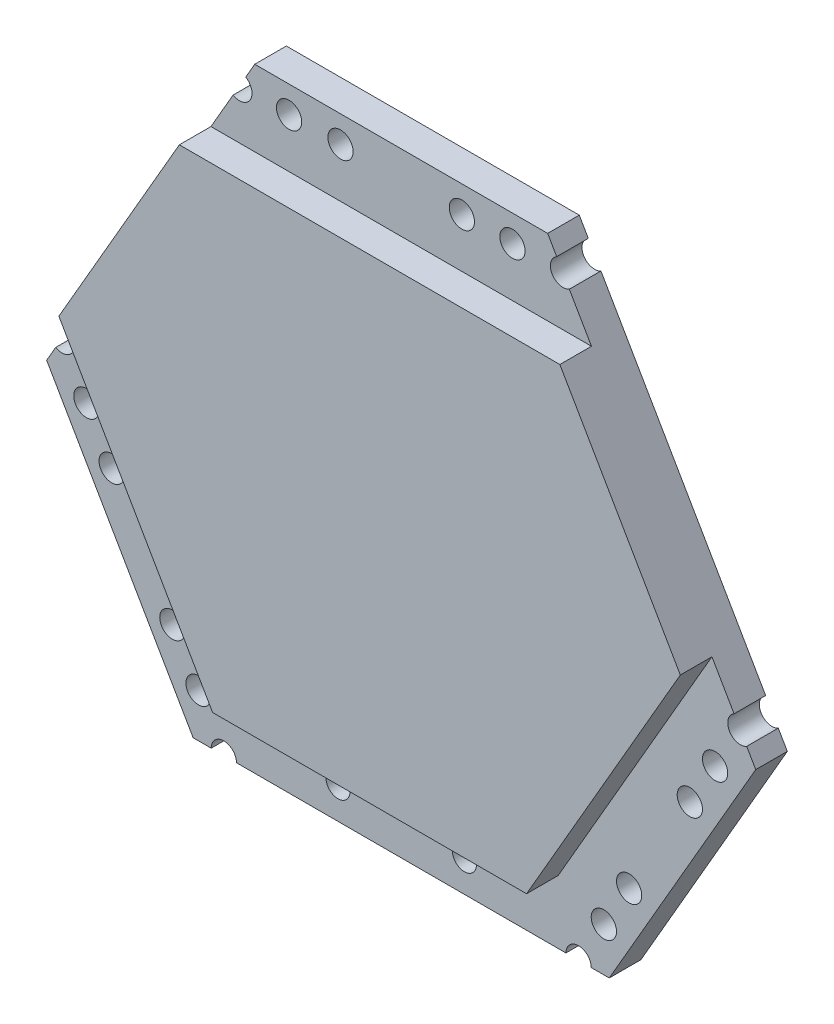
SolidWorks part; units mm, degrees
material "ABS"
ref_plane "前基準面" through (0, 0, 0) normal (0, 0, 1) x (1, 0, 0)
ref_plane "上基準面" through (0, 0, 0) normal (0, 1, 0) x (1, 0, 0)
ref_plane "右基準面" through (0, 0, 0) normal (1, 0, 0) x (0, 0, -1)
sketch "草圖1" plane through (0, 0, 0) normal (0, 0, 1) x (1, 0, 0)
  line L0 (29.3027, 33.7186) -> (37.3027, 33.7186) construction
  line L1 (45.3027, 33.7186) -> (-5.8973, 33.7186)
  line L2 (-5.8973, 33.7186) -> (-33.9573, -14.8827)
  line L3 (-33.9573, -14.8827) -> (-5.8973, 33.7186)
  line L7 (-33.9573, -14.8827) -> (-8.3573, -59.2232)
  line L8 (-8.3573, -59.2232) -> (-33.9573, -14.8827)
  line L9 (-8.3573, -59.2232) -> (47.7627, -59.2232)
  line L10 (47.7627, -59.2232) -> (73.3627, -14.8827)
  line L11 (73.3627, -14.8827) -> (45.3027, 33.7186)
  line L12 (73.3627, -14.8827) -> (69.3627, -21.8109) construction
  line L13 (-10.3973, 37.9244) -> (49.8027, 37.9244)
  line L14 (-10.3973, 37.9244) -> (-10.3973, 25.9244)
  line L15 (-10.3973, 25.9244) -> (49.8027, 25.9244)
  line L16 (49.8027, 37.9244) -> (49.8027, 25.9244)
  line L17 (-29.4573, -7.0885) -> (0.6427, -59.2232)
  line L18 (0.6427, -59.2232) -> (-9.7496, -65.2232)
  line L19 (-9.7496, -65.2232) -> (-39.8496, -13.0885)
  line L20 (-39.8496, -13.0885) -> (-29.4573, -7.0885)
  line L21 (55.7627, -45.3668) -> (51.7627, -52.295) construction
  line L22 (68.8627, -7.0885) -> (38.7627, -59.2232)
  line L23 (38.7627, -59.2232) -> (49.155, -65.2232)
  line L24 (49.155, -65.2232) -> (79.255, -13.0885)
  line L25 (79.255, -13.0885) -> (68.8627, -7.0885)
  circle A0 centre (-5.8973, 33.7186) radius 2
  circle A1 centre (1.9623, 33.7186) radius 2
  circle A2 centre (10.1027, 33.7186) radius 2
  circle A4 centre (29.3027, 33.7186) radius 2
  circle A8 centre (-33.9573, -14.8827) radius 2
  circle A9 centre (-30.0977, -21.8109) radius 2
  circle A10 centre (-26.0977, -28.7391) radius 2
  circle A12 centre (-16.4977, -45.3668) radius 2
  circle A13 centre (-12.3573, -52.295) radius 2
  circle A14 centre (-8.3573, -59.2232) radius 2
  circle A15 centre (47.7627, -59.2232) radius 2
  circle A18 centre (55.7627, -45.3668) radius 2
  circle A22 centre (37.3027, 33.7186) radius 2
  circle A23 centre (45.3027, 33.7186) radius 2
  circle A24 centre (73.3627, -14.8827) radius 2
  circle A25 centre (69.3627, -21.8109) radius 2
  circle A26 centre (65.3627, -28.7391) radius 2
  circle A27 centre (51.7627, -52.295) radius 2
  dimension "D1" = 4
  dimension "D6" = 4
  dimension "D10" = 4
  dimension "D13" = 19.2
  dimension "D11" = 4
  dimension "D15" = 19.2
  dimension "D7" = 19.2
  dimension "D17" = 8
  dimension "D2" = 8
  dimension "D3" = 120
  dimension "D4" = 120
  dimension "D5" = 56.12
  dimension "D8" = 120
  dimension "D9" = 56.12
  dimension "D12" = 8
  dimension "D16" = 56.12
  dimension "D18" = 4.5
  dimension "D19" = 4.5
  dimension "D20" = 60.2
  dimension "D21" = 12
  dimension "D22" = 90
  dimension "D23" = 180
  dimension "D24" = 12
  dimension "D25" = 4.5
  dimension "D26" = 4.5
  dimension "D27" = 8
  dimension "D28" = 12
  dimension "D29" = 60.2
  dimension "D30" = 90
  dimension "D31" = 4.5
  dimension "D14" = 3
extrude "填料-伸長4" add sketch "草圖1" along normal blind 10 contours L22 L11 L15 L3 L17 L9 | A23 L1 A22 A4 A2 A1 A0 L3 L15 L11 | A23 L11 L16 L13 L14 L3 A0 L1 A1 A2 A4 A22 | A14 L8 A13 A12 A10 A9 A8 L2 L20 L19 L18 L9 | A14 L9 L17 L2 A8 L8 A9 A10 A12 A13 | A27 L10 A15 L9 L23 L24 L25 L11 A24 A25 A26 A18 | A27 L10 A18 A26 A25 A24 L11 L22 L9 A15
sketch "草圖4" plane through (0, 0, 10) normal (0, 0, 1) x (1, 0, 0)
  line L0 (38.7627, -59.2232) -> (49.155, -65.2232)
  line L1 (-10.3973, 37.9244) -> (49.8027, 37.9244)
  line L2 (-10.3973, 37.9244) -> (-10.3973, 25.9244)
  line L3 (-10.3973, 25.9244) -> (49.8027, 25.9244)
  line L4 (49.8027, 37.9244) -> (49.8027, 25.9244)
  line L5 (38.7627, -59.2232) -> (68.8722, -7.072)
  line L6 (49.155, -65.2232) -> (79.2645, -13.072)
  line L7 (68.8722, -7.072) -> (79.2645, -13.072)
  line L8 (-29.4573, -7.0885) -> (-39.8496, -13.0885)
  line L9 (-29.4573, -7.0885) -> (0.9201, -59.7038)
  line L10 (-39.8496, -13.0885) -> (-9.4722, -65.7038)
  line L11 (0.9201, -59.7038) -> (-9.4722, -65.7038)
extrude "除料-伸長2" cut sketch "草圖4" against normal blind 5
sketch "草圖7" plane through (-19.0236, 10.9833, 0) normal (-0.866, 0.5, 0) x (0, 0, 1)
  line L0 (0, -5.7866) -> (10, -5.7866)
  line L1 (0, -5.7866) -> (0, 46.268)
  line L2 (10, -5.7866) -> (10, 46.268)
  line L3 (0, 46.268) -> (10, 46.268)
  line L4 (0, 17.2525) -> (0, -20.8675) construction
  line L5 (10, 17.2525) -> (10, -20.8675) construction
  line L6 (0, -5.7866) -> (10, -5.7866)
  line L7 (0, -5.7866) -> (0, -53.8162)
  line L8 (10, -5.7866) -> (10, -53.8162)
  line L9 (0, -53.8162) -> (10, -53.8162)
  line M2 (0, -20.8675) -> (5, -20.8675)
  line M3 (5, -20.8675) -> (10, -20.8675)
  line M5 (10, 17.2525) -> (5, 17.2525)
  line M6 (5, 17.2525) -> (0, 17.2525)
extrude "除料-伸長9" cut sketch "草圖7" along direction (-0.866, 0.5, 0) on the side of the normal through all contours L7 L9 L8 M3 M2 | L3 L1 L2 M6 M5
sketch "草圖12" plane through (48.5776, 28.0463, 0) normal (0.866, 0.5, 0) x (0, 0, -1)
  line L0 (0, -23.6856) -> (-10, -23.6856)
  line L1 (0, -23.6856) -> (0, -70.3801)
  line L2 (-10, -23.6856) -> (-10, -70.3801)
  line L3 (0, -70.3801) -> (-10, -70.3801)
  line L4 (0, -40.5702) -> (0, -2.4502) construction
  line L5 (-10, -40.5702) -> (-10, -2.4502) construction
  line L6 (0, -23.6856) -> (-10, -23.6856)
  line L7 (0, -23.6856) -> (0, 27.878)
  line L8 (-10, -23.6856) -> (-10, 27.878)
  line L9 (0, 27.878) -> (-10, 27.878)
  line M2 (0, -2.4502) -> (-5, -2.4502)
  line M3 (-5, -2.4502) -> (-10, -2.4502)
  line M5 (-10, -40.5702) -> (-5, -40.5702)
  line M6 (-5, -40.5702) -> (0, -40.5702)
extrude "除料-伸長12" cut sketch "草圖12" along normal through all contours L3 L1 L2 M6 M5 | L7 L9 L8 M3 M2
sketch "草圖13" plane through (0, -59.2232, 0) normal (0, -1, 0) x (1, 0, 0)
  line L0 (19.7027, 10) -> (19.7027, 0)
  line L1 (19.7027, 10) -> (-25.3386, 10)
  line L2 (19.7027, 0) -> (-25.3386, 0)
  line L3 (-25.3386, 10) -> (-25.3386, 0)
  line L4 (0.6427, 10) -> (38.7627, 10) construction
  line L5 (0.6427, 0) -> (38.7627, 0) construction
  line L6 (19.7027, 10) -> (19.7027, 0)
  line L7 (19.7027, 10) -> (66.2602, 10)
  line L8 (19.7027, 0) -> (66.2602, 0)
  line L9 (66.2602, 10) -> (66.2602, 0)
  line M2 (38.7627, 0) -> (38.7627, 5)
  line M3 (38.7627, 5) -> (38.7627, 10)
  line M5 (0.6427, 10) -> (0.6427, 5)
  line M6 (0.6427, 5) -> (0.6427, 0)
extrude "除料-伸長13" cut sketch "草圖13" along normal through all contours L9 L7 L8 M3 M2 | L1 L3 L2 M6 M5
sketch "草圖17" plane through (0, 0, 0) normal (0, 0, -1) x (-1, 0, 0)
  text T0 "Buttom" font "Impact" height in points 26
extrude "除料-伸長15" cut sketch "草圖17" against normal blind 2
sketch "草圖19" plane through (0, 0, 10) normal (0, 0, 1) x (1, 0, 0)
  line L0 (38.7627, -59.2232) -> (44.5362, -49.2232)
  line L1 (68.8627, -7.0885) -> (38.7627, -59.2232) construction
  line L2 (44.5362, -49.2232) -> (-5.1308, -49.2232)
  line L3 (0.6427, -59.2232) -> (-29.4573, -7.0885) construction
  line L4 (-5.1308, -49.2232) -> (0.6427, -59.2232)
  line L5 (0.6427, -59.2232) -> (38.7627, -59.2232)
  dimension "D1" = 60
  dimension "D2" = 10
sketch "草圖20" plane through (0, 0, 10) normal (0, 0, 1) x (1, 0, 0)
  line L0 (0.6427, -59.2232) -> (38.7627, -59.2232) construction
  circle A0 centre (29.7027, -54.2232) radius 1.9
  circle A1 centre (9.7027, -54.2232) radius 1.9
  dimension "D1" = 5
  dimension "D2" = 5
  dimension "D3" = 3.8
  dimension "D4" = 3.8
  dimension "D5" = 20
  dimension "D6" = 9.06
extrude "除料-伸長18" cut sketch "草圖20" against normal blind 10
extrude "除料-伸長19" cut sketch "草圖19" against normal blind 5
